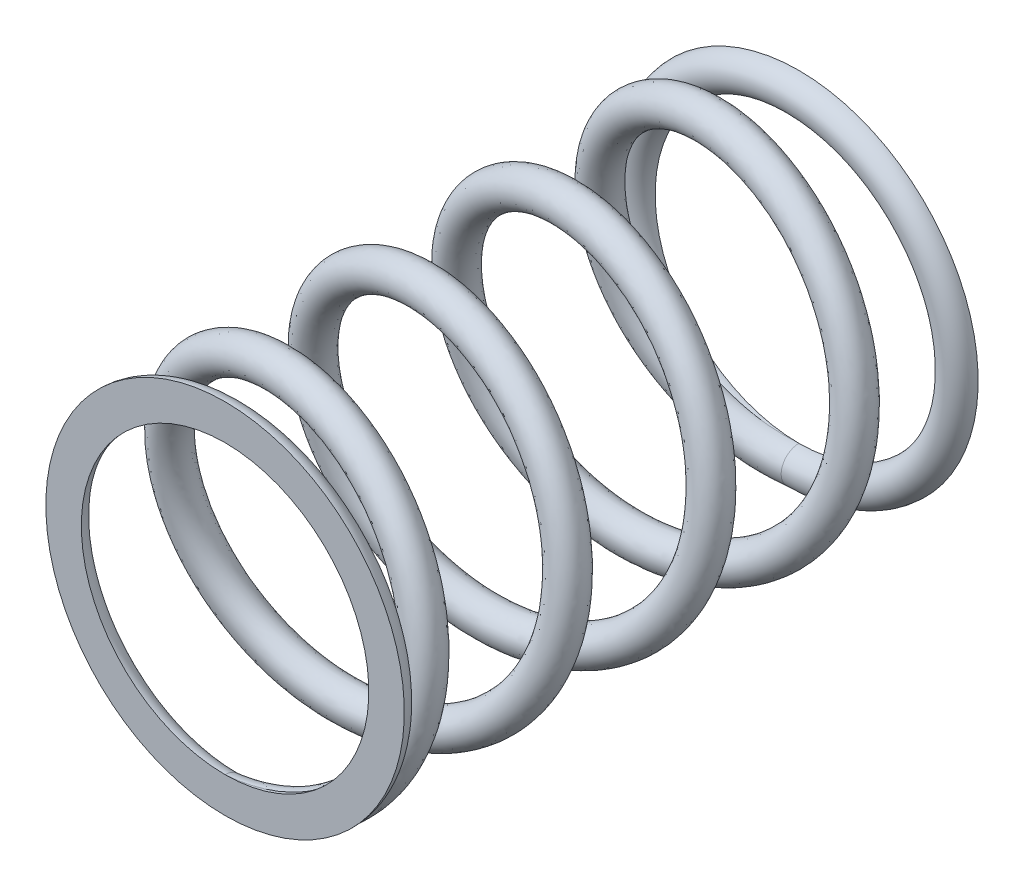
SolidWorks part; units mm, degrees
material "Nichel"
ref_plane "Piano frontale" through (0, 0, 0) normal (0, 0, 1) x (1, 0, 0)
ref_plane "Piano superiore" through (0, 0, 0) normal (0, 1, 0) x (1, 0, 0)
ref_plane "Piano destro" through (0, 0, 0) normal (1, 0, 0) x (0, 0, -1)
sketch "Schizzo1" plane through (0, 0, 0) normal (0, 0, 1) x (1, 0, 0)
  circle A0 centre (0, 0) radius 4.55
  dimension "D1" = 9.1
curve "Elica/Spirale1" pitch 4.0421 height 16.1684 turns 4
sketch "Schizzo19" plane through (0, 0, 0) normal (1, 0, 0) x (0, 0, -1)
  line L0 (0, -4.55) -> (0, 0) construction
  circle A0 centre (0, -4.55) radius 0.5
  spline S0 degree 3 poles (0, -4.55) (-0.0837, -4.55) (-0.2529, -4.3131) (-0.5052, -3.3011) (-0.7579, -1.7865) (-1.0105, 0) (-1.2632, 1.7865) (-1.5158, 3.3011) (-1.7684, 4.3131) (-2.0211, 4.6685) (-2.2737, 4.3131) (-2.5263, 3.3011) (-2.8632, 1.2817) (-3.2, -1.2817) (-3.5368, -3.3011) (-3.7895, -4.3131) (-4.0421, -4.6685) (-4.2947, -4.3131) (-4.5474, -3.3011) (-4.8842, -1.2817) (-5.221, 1.2817) (-5.5579, 3.3011) (-5.8105, 4.3131) (-6.0632, 4.6685) (-6.3158, 4.3131) (-6.5684, 3.3011) (-6.9053, 1.2817) (-7.2421, -1.2817) (-7.5789, -3.3011) (-7.8316, -4.3131) (-8.0842, -4.6685) (-8.3368, -4.3131) (-8.5895, -3.3011) (-8.9263, -1.2817) (-9.2632, 1.2817) (-9.6, 3.3011) (-9.8526, 4.3131) (-10.1053, 4.6685) (-10.3579, 4.3131) (-10.6105, 3.3011) (-10.9474, 1.2817) (-11.2842, -1.2817) (-11.621, -3.3011) (-11.8737, -4.3131) (-12.1263, -4.6685) (-12.3789, -4.3131) (-12.6316, -3.3011) (-12.9684, -1.2817) (-13.3053, 1.2817) (-13.6421, 3.3011) (-13.8947, 4.3131) (-14.1474, 4.6685) (-14.4, 4.3131) (-14.6526, 3.3011) (-14.9053, 1.7865) (-15.1579, 0) (-15.4105, -1.7865) (-15.6632, -3.3011) (-15.9155, -4.3131) (-16.0847, -4.55) (-16.1684, -4.55) knots 0 0 0 0 0.015625 0.03125 0.046875 0.0625 0.078125 0.09375 0.109375 0.125 0.140625 0.15625 0.171875 0.203125 0.21875 0.234375 0.25 0.265625 0.28125 0.296875 0.328125 0.34375 0.359375 0.375 0.390625 0.40625 0.421875 0.453125 0.46875 0.484375 0.5 0.515625 0.53125 0.546875 0.578125 0.59375 0.609375 0.625 0.640625 0.65625 0.671875 0.703125 0.71875 0.734375 0.75 0.765625 0.78125 0.796875 0.828125 0.84375 0.859375 0.875 0.890625 0.90625 0.921875 0.9375 0.953125 0.96875 0.984375 1 1 1 1 construction
  dimension "D1" = 1
sweep "Sweep1" add profiles "Schizzo19" path "Elica/Spirale1"
sketch "Schizzo8" plane through (0, 0, 0) normal (0, 1, 0) x (1, 0, 0)
  line L0 (0, 0) -> (0, -17.2452) construction
sketch "Schizzo17" plane through (0, 0, 0) normal (-1, 0, 0) x (0, 0, 1)
  line L0 (-1000, 0) -> (49000, 0) construction
  circle A1 centre (16.1684, -4.55) radius 0.5
  circle A2 centre (16.1684, -4.55) radius 0.5
  dimension "D1" = 0
revolve "Rivoluzione3" add sketch "Schizzo17" angle 360 about L0
sketch "Schizzo18" plane through (0, 0, 0) normal (1, 0, 0) x (0, 0, -1)
  line L0 (-1000, 0) -> (49000, 0) construction
  circle A1 centre (0, -4.55) radius 0.5
  circle A2 centre (0, -4.55) radius 0.5
  dimension "D1" = 0
revolve "Rivoluzione4" add sketch "Schizzo18" angle 360 about L0
sketch "Schizzo23" plane through (0, 0, 0) normal (0, 1, 0) x (1, 0, 0)
  line L0 (4.55, 0.5) -> (-4.55, 0.5) construction
  line L1 (-5.05, 0) -> (5.05, 0)
  line L2 (-5.05, 0) -> (-5.05, 0.5)
  line L3 (-5.05, 0.5) -> (5.05, 0.5)
  line L4 (5.05, 0) -> (5.05, 0.5)
  line L5 (-5.05, 0) -> (5.05, 0.5) construction
  line L6 (-5.05, 0.5) -> (5.05, 0) construction
  line L7 (-4.55, -16.6684) -> (4.55, -16.6684) construction
  line L8 (5.05, -16.1684) -> (-5.05, -16.1684)
  line L9 (5.05, -16.1684) -> (5.05, -16.6684)
  line L10 (5.05, -16.6684) -> (-5.05, -16.6684)
  line L11 (-5.05, -16.1684) -> (-5.05, -16.6684)
  line L12 (5.05, -16.1684) -> (-5.05, -16.6684) construction
  line L13 (5.05, -16.6684) -> (-5.05, -16.1684) construction
  arc A0 (-4.55, 0.5) -> (-4.55, -0.5) centre (-4.55, 0) ccw construction
  arc A1 (4.55, -0.5) -> (4.55, 0.5) centre (4.55, 0) ccw construction
  arc A2 (4.55, -16.6684) -> (4.55, -15.6684) centre (4.55, -16.1684) ccw construction
  arc A3 (-4.55, -15.6684) -> (-4.55, -16.6684) centre (-4.55, -16.1684) ccw construction
  point P4 (0, 0.25)
  point P19 (0, -16.4184)
extrude "Taglio-Estrusione1" cut sketch "Schizzo23" against normal through all both and the other way through all
